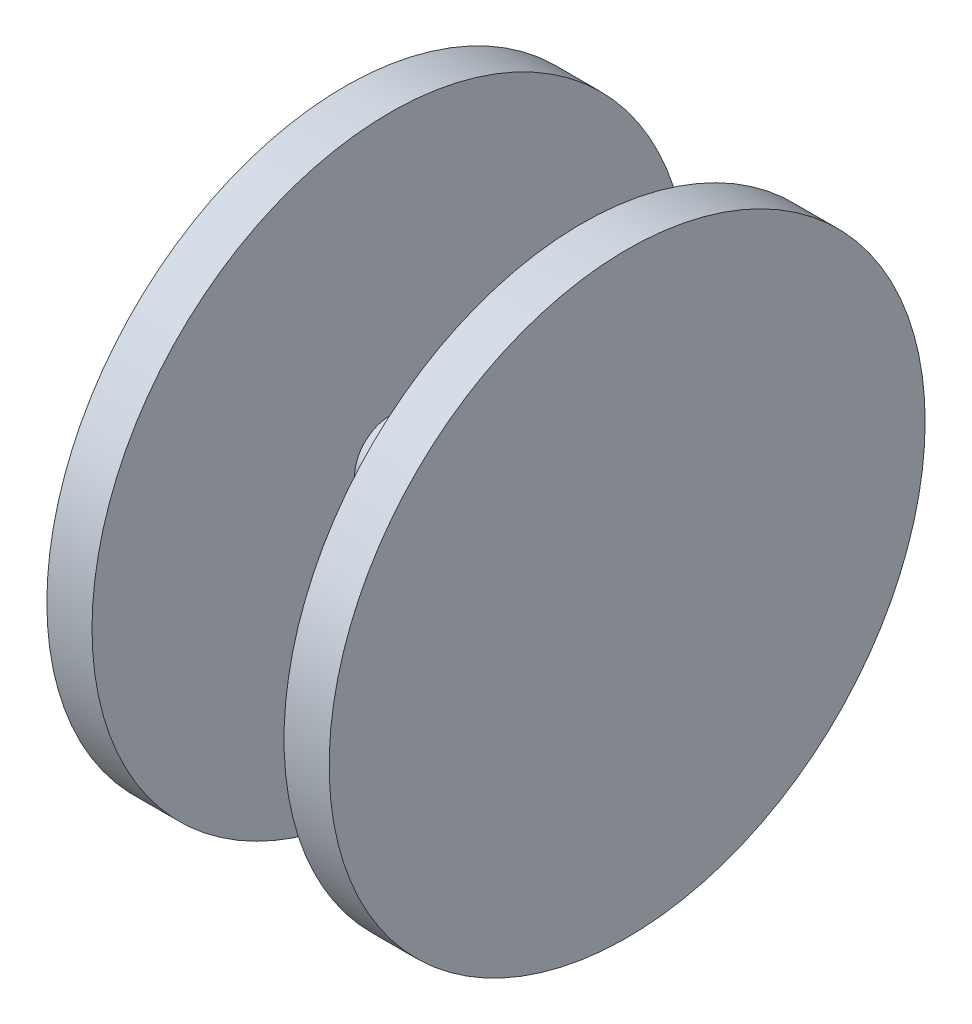
SolidWorks part; units mm, degrees
ref_plane "Front Plane" through (0, 0, 0) normal (0, 0, 1) x (1, 0, 0)
ref_plane "Top Plane" through (0, 0, 0) normal (0, 1, 0) x (1, 0, 0)
ref_plane "Right Plane" through (0, 0, 0) normal (1, 0, 0) x (0, 0, -1)
sketch "Sketch4" plane through (0, 0, 0) normal (1, 0, 0) x (0, 0, -1)
  circle A0 centre (0, 0) radius 41.91
  dimension "D1" = 83.82
extrude "Boss-Extrude1" add sketch "Sketch4" along normal blind 6.35 contours A0
sketch "Sketch5" plane through (0, 0, 0) normal (-1, 0, 0) x (0, 0, 1)
  circle A0 centre (0, 0) radius 5
extrude "Boss-Extrude4" add sketch "Sketch5" along normal blind 27
sketch "Sketch7" plane through (-27, 0, 0) normal (-1, 0, 0) x (0, 0, 1)
  circle A0 centre (0, 0) radius 41.91
  circle A1 centre (0, 0) radius 41.91 construction
extrude "Boss-Extrude5" add sketch "Sketch7" along normal blind 6.35
